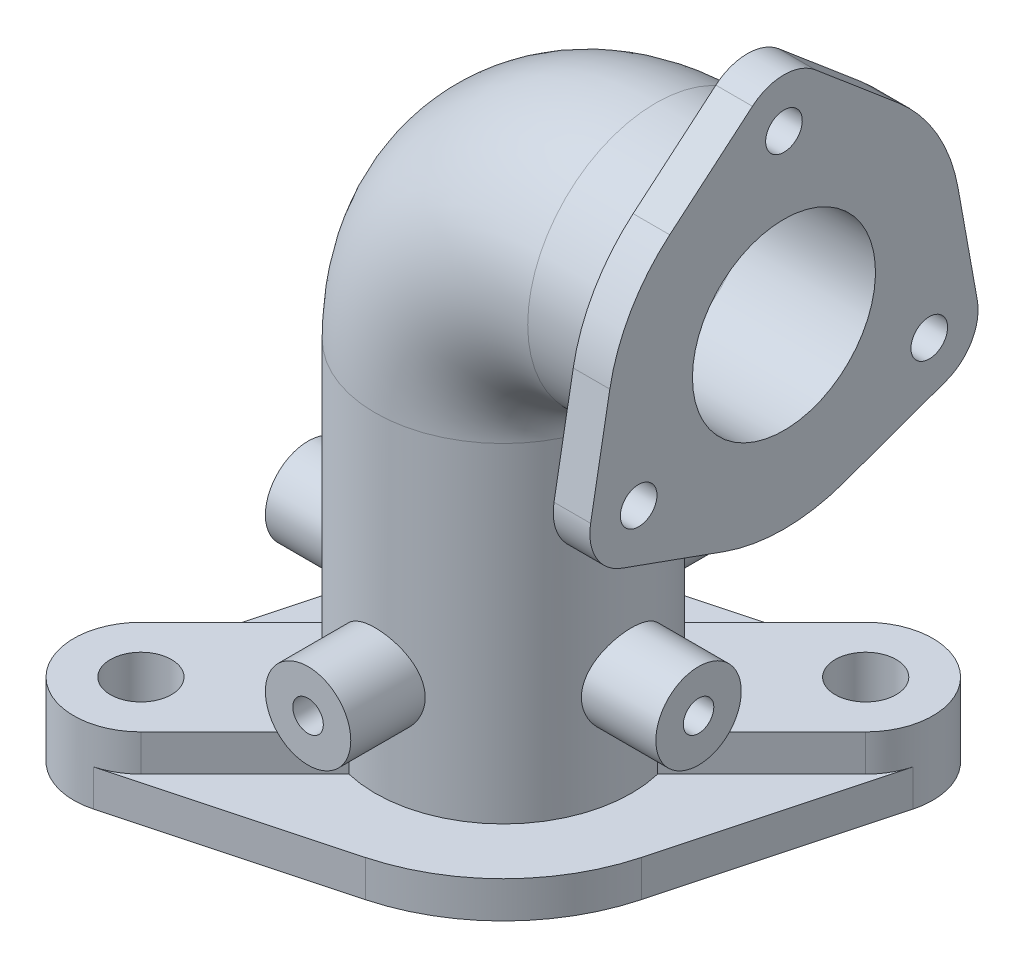
SolidWorks part; units mm, degrees
ref_plane "Front Plane" through (0, 0, 0) normal (0, 0, 1) x (1, 0, 0)
ref_plane "Top Plane" through (0, 0, 0) normal (0, 1, 0) x (1, 0, 0)
ref_plane "Right Plane" through (0, 0, 0) normal (1, 0, 0) x (0, 0, -1)
sketch "Sketch1" plane through (0, 0, 0) normal (0, 0, 1) x (1, 0, 0)
  line L0 (0, 0) -> (0, 60)
  line L1 (25, 85) -> (46, 85)
  arc A0 (0, 60) -> (25, 85) centre (25, 60) cw
  dimension "D3" = 25
  dimension "D1" = 60
  dimension "D2" = 21
sketch "Sketch2" plane through (0, 0, 0) normal (0, 1, 0) x (1, 0, 0)
  circle A0 centre (0, 0) radius 21
  circle A1 centre (0, 0) radius 15
  dimension "D1" = 42
  dimension "D2" = 30
sweep "Sweep1" add profiles "Sketch2" path "Sketch1"
sketch "Sketch4" plane through (46, 0, 0) normal (1, 0, 0) x (0, 0, -1)
  line L0 (0, 85) -> (0, 112.5) construction
  line L1 (5.1652, 118.6091) -> (18.7238, 107.1455)
  line L2 (-5.1652, 118.6091) -> (-18.7238, 107.1455)
  line L3 (26.5237, 63.7223) -> (9.8167, 57.712)
  line L4 (31.6889, 72.6686) -> (28.5404, 90.1425)
  line L5 (-31.6889, 72.6686) -> (-28.5404, 90.1425)
  line L6 (-26.5237, 63.7223) -> (-9.8167, 57.712)
  arc A0 (-9.8167, 57.712) -> (9.8167, 57.712) centre (0, 85) ccw
  circle A1 centre (0, 85) radius 27.5 construction
  arc A2 (5.1652, 118.6091) -> (-5.1652, 118.6091) centre (0, 112.5) ccw
  circle A3 centre (0, 112.5) radius 3
  arc A4 (26.5237, 63.7223) -> (31.6889, 72.6686) centre (23.8157, 71.25) ccw
  circle A5 centre (23.8157, 71.25) radius 3
  arc A6 (-31.6889, 72.6686) -> (-26.5237, 63.7223) centre (-23.8157, 71.25) ccw
  circle A7 centre (-23.8157, 71.25) radius 3
  arc A8 (-18.7238, 107.1455) -> (-28.5404, 90.1425) centre (0, 85) ccw
  arc A9 (28.5404, 90.1425) -> (18.7238, 107.1455) centre (0, 85) ccw
  circle A10 centre (0, 85) radius 15 construction
  circle A11 centre (0, 85) radius 15
  dimension "D1" = 58
  dimension "D2" = 55
  dimension "D3" = 16
  dimension "D4" = 6
  dimension "D5" = 3
extrude "Boss-Extrude1" add sketch "Sketch4" against normal blind 6
sketch "Sketch5" plane through (0, 0, 0) normal (0, -1, 0) x (1, 0, 0)
  line L0 (0, 0) -> (29.6985, -29.6985) construction
  line L1 (0, 0) -> (0, -43.6462) construction
  line L2 (0, 0) -> (26.1327, 26.1327) construction
  line L3 (0, 0) -> (-29.6985, 29.6985) construction
  line L4 (-40.3237, 26.8515) -> (-30.9096, -8.2822)
  line L5 (-8.2822, -30.9096) -> (26.8515, -40.3237)
  line L6 (30.9096, 8.2822) -> (40.3237, -26.8515)
  line L7 (-26.8515, 40.3237) -> (8.2822, 30.9096)
  arc A0 (-30.9096, -8.2822) -> (-8.2822, -30.9096) centre (0, 0) ccw
  arc A1 (-26.8515, 40.3237) -> (-40.3237, 26.8515) centre (-29.6985, 29.6985) ccw
  arc A2 (26.8515, -40.3237) -> (40.3237, -26.8515) centre (29.6985, -29.6985) ccw
  arc A3 (30.9096, 8.2822) -> (8.2822, 30.9096) centre (0, 0) ccw
  circle A4 centre (0, 0) radius 15 construction
  circle A5 centre (0, 0) radius 15
  dimension "D1" = 64
  dimension "D2" = 22
  dimension "D3" = 22
  dimension "D4" = 42
  dimension "D5" = 45
  dimension "D6" = 42
extrude "Boss-Extrude2" add sketch "Sketch5" against normal blind 6
sketch "Sketch7" plane through (0, 6, 0) normal (0, 1, 0) x (1, 0, 0)
  line L0 (-37.4767, -21.9203) -> (-20.4273, -4.8709)
  line L1 (-21.9203, -37.4767) -> (-4.8709, -20.4273)
  line L2 (20.4273, 4.8709) -> (37.4767, 21.9203)
  line L3 (4.8709, 20.4273) -> (21.9203, 37.4767)
  circle A0 centre (0, 0) radius 21 construction
  arc A1 (-20.4273, -4.8709) -> (-4.8709, -20.4273) centre (0, 0) ccw
  arc A3 (-37.4767, -21.9203) -> (-21.9203, -37.4767) centre (-29.6985, -29.6985) ccw
  arc A4 (37.4767, 21.9203) -> (21.9203, 37.4767) centre (29.6985, 29.6985) ccw
  arc A5 (40.3237, 26.8515) -> (26.8515, 40.3237) centre (29.6985, 29.6985) ccw construction
  arc A6 (-40.3237, -26.8515) -> (-26.8515, -40.3237) centre (-29.6985, -29.6985) ccw construction
  arc A7 (20.4273, 4.8709) -> (4.8709, 20.4273) centre (0, 0) ccw
extrude "Boss-Extrude3" add sketch "Sketch7" along normal blind 6
hole_wizard "Hole1" positions "Sketch8" profile "Sketch9" legacy end condition up to next
sketch "Sketch8" plane through (0, 12, 0) normal (0, 1, 0) x (1, 0, 0)
  point P0 (-29.6985, -29.6985)
  point P3 (29.6985, 29.6985)
sketch "Sketch9" plane through (-29.6985, 12, 29.6985) normal (1, 0, 0) x (0, 0, 1)
  line L0 (0, 0) -> (0, 12)
  line L1 (0, 12) -> (5, 12)
  line L2 (5, 12) -> (5, 0)
  line L3 (5, 0) -> (0, 0)
  line L4 (0, 110) -> (0, -10) construction
  dimension "Diameter" = 10
  dimension "Depth" = 12
ref_plane "Plane1" through (0, 0, 32) normal (0, 0, 1) x (1, 0, 0)
sketch "Sketch10" plane through (0, 0, 32) normal (0, 0, 1) x (1, 0, 0)
  circle A0 centre (0, 22.5) radius 7
  dimension "D1" = 14
  dimension "D2" = 22.5
extrude "Boss-Extrude5" add sketch "Sketch10" against normal up to next
pattern_circular "CirPattern1" count 4 over 360 about axis through (0, 0, 0) along (0, 1, 0) of "Boss-Extrude5"
hole_wizard "Hole2" positions "Sketch11" profile "Sketch12" legacy
sketch "Sketch11" plane through (0, 0, 32) normal (0, 0, 1) x (1, 0, 0)
  point P0 (0, 22.5)
sketch "Sketch12" plane through (0, 22.5, 32) normal (1, 0, 0) x (0, -1, 0)
  line L0 (0, 0) -> (0, 17)
  line L1 (0, 17) -> (2.5, 17)
  line L2 (2.5, 17) -> (2.5, 0)
  line L3 (2.5, 0) -> (0, 0)
  line L4 (0, 110) -> (0, -10) construction
  dimension "Diameter" = 5
  dimension "Depth" = 17
pattern_circular "CirPattern2" count 4 over 360 about axis through (0, 0, 0) along (0, 1, 0) of "Hole2"
